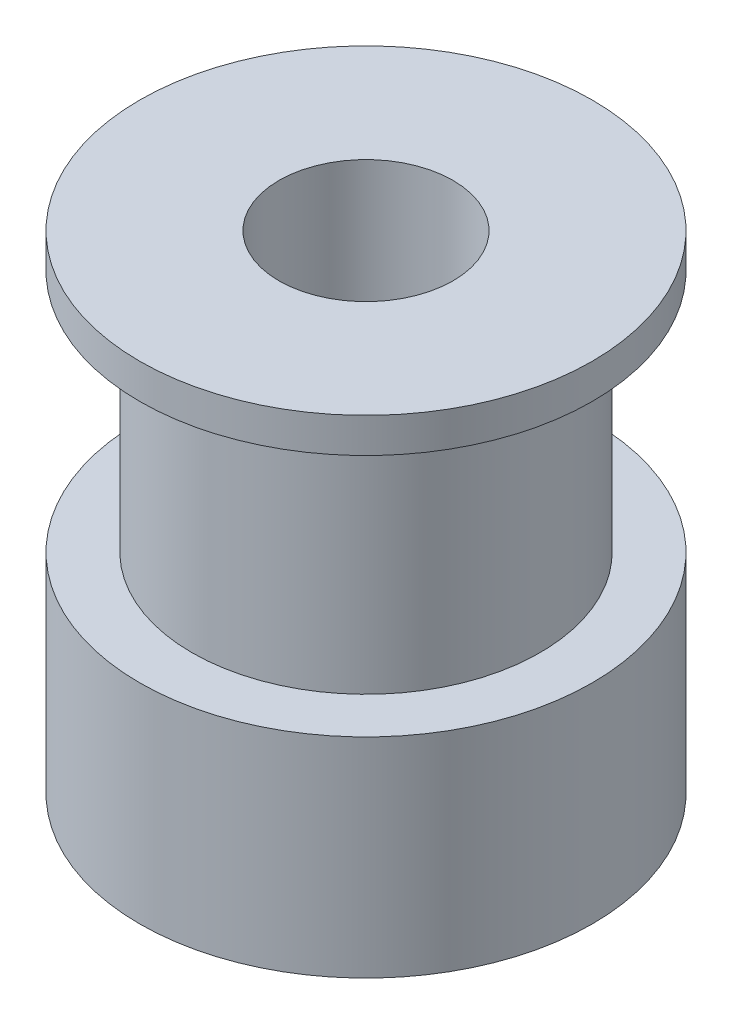
SolidWorks part; units mm, degrees
ref_plane "Front Plane" through (0, 0, 0) normal (0, 0, 1) x (1, 0, 0)
ref_plane "Top Plane" through (0, 0, 0) normal (0, 1, 0) x (1, 0, 0)
ref_plane "Right Plane" through (0, 0, 0) normal (1, 0, 0) x (0, 0, -1)
sketch "Sketch1" plane through (0, 0, 0) normal (0, 1, 0) x (1, 0, 0)
  circle A0 centre (0, 0) radius 6.5
  dimension "D1" = 13
extrude "Boss-Extrude1" add sketch "Sketch1" along normal blind 6
sketch "Sketch2" plane through (0, 6, 0) normal (0, 1, 0) x (1, 0, 0)
  circle A0 centre (0, 0) radius 5
  dimension "D1" = 10
extrude "Boss-Extrude2" add sketch "Sketch2" along normal blind 7
sketch "Sketch3" plane through (0, 13, 0) normal (0, 1, 0) x (1, 0, 0)
  circle A0 centre (0, 0) radius 6.5
extrude "Boss-Extrude3" add sketch "Sketch3" along normal blind 1
sketch "Sketch4" plane through (0, 14, 0) normal (0, 1, 0) x (1, 0, 0)
  circle A0 centre (0, 0) radius 2.5
  dimension "D1" = 5
extrude "Cut-Extrude1" cut sketch "Sketch4" against normal blind 30
